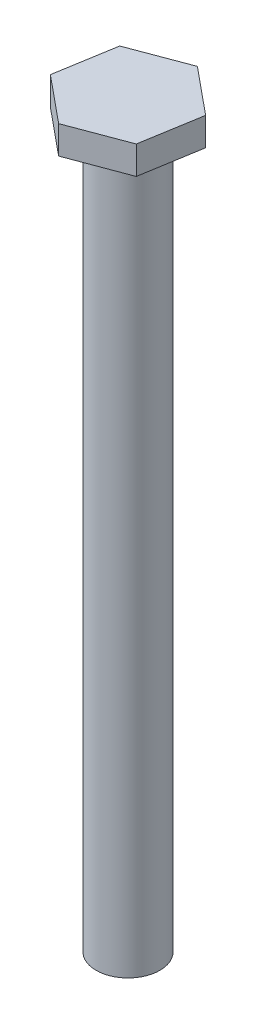
SolidWorks part; units mm, degrees
material "AISI 316 Stainless Steel Sheet (SS)"
ref_plane "Front Plane" through (0, 0, 0) normal (0, 0, 1) x (1, 0, 0)
ref_plane "Top Plane" through (0, 0, 0) normal (0, 1, 0) x (1, 0, 0)
ref_plane "Right Plane" through (0, 0, 0) normal (1, 0, 0) x (0, 0, -1)
sketch "Sketch1" plane through (0, 0, 0) normal (0, 1, 0) x (1, 0, 0)
  circle A0 centre (0, 0) radius 7.9375
  dimension "D1" = 15.875
extrude "Shaft" add sketch "Sketch1" against normal blind 177.8
sketch "Sketch2" plane through (0, 0, 0) normal (0, 1, 0) x (1, 0, 0)
  line L1 (11.595, -9.5335) -> (14.0538, 5.2748)
  line L2 (14.0538, 5.2748) -> (2.4588, 14.8084)
  line L3 (2.4588, 14.8084) -> (-11.595, 9.5335)
  line L4 (-11.595, 9.5335) -> (-14.0538, -5.2748)
  line L5 (-14.0538, -5.2748) -> (-2.4588, -14.8084)
  line L6 (-2.4588, -14.8084) -> (11.595, -9.5335)
  circle A0 centre (0, 0) radius 13 construction
  dimension "D1" = 13
extrude "Head" add sketch "Sketch2" along normal blind 7
equation "\"boltLength\"= 7in"
equation "\"boltDiameter\"= 5in / 8"
equation "\"D1@Sketch1\"=\"boltDiameter\""
equation "\"D1@Shaft\" = \"boltLength\""
